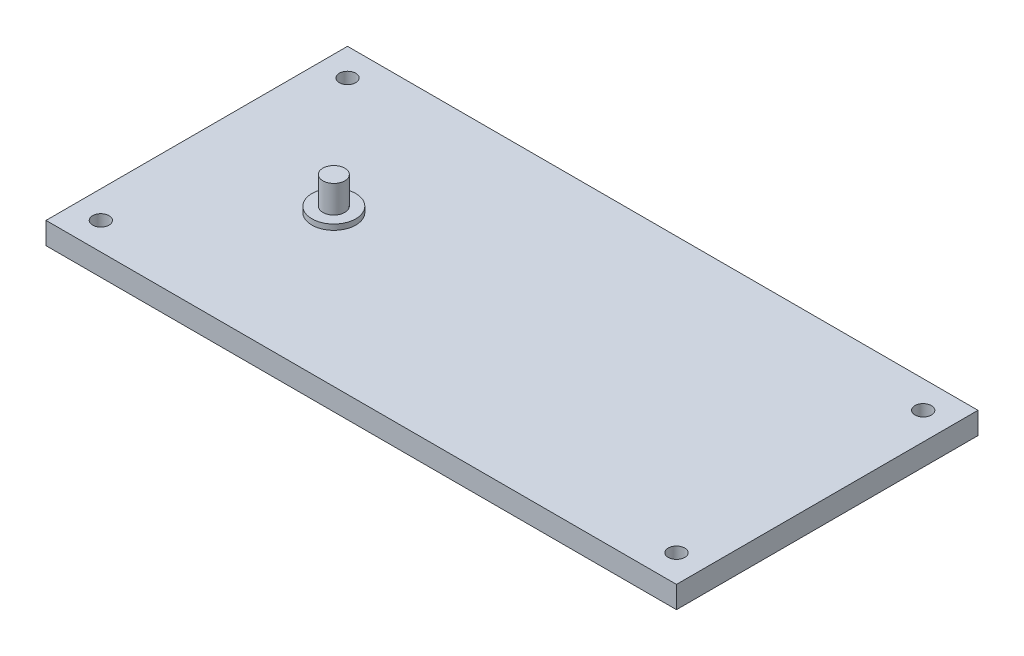
SolidWorks part; units mm, degrees
ref_plane "前视基准面" through (0, 0, 0) normal (0, 0, 1) x (1, 0, 0)
ref_plane "上视基准面" through (0, 0, 0) normal (0, 1, 0) x (1, 0, 0)
ref_plane "右视基准面" through (0, 0, 0) normal (1, 0, 0) x (0, 0, -1)
other "Configuration Table"
sketch "草图1" plane through (0, 0, 0) normal (0, 1, 0) x (1, 0, 0)
  line L1 (-115, 55) -> (115, 55)
  line L2 (-115, 55) -> (-115, -55)
  line L3 (-115, -55) -> (115, -55)
  line L4 (115, 55) -> (115, -55)
  line L5 (-115, 55) -> (115, -55) construction
  line L6 (-115, -55) -> (115, 55) construction
  point P0 (0, 0)
  dimension "D1" = 110
  dimension "D2" = 230
extrude "凸台-拉伸1" add sketch "草图1" along normal blind 8
sketch "草图2" plane through (0, 8, 0) normal (0, 1, 0) x (1, 0, 0)
  circle A0 centre (-65, 0) radius 8
  dimension "D1" = 65
  dimension "D2" = 16
extrude "凸台-拉伸2" add sketch "草图2" along normal blind 2 contours A0
sketch "草图3" plane through (0, 10, 0) normal (0, 1, 0) x (1, 0, 0)
  circle A0 centre (-65, 0) radius 4
  circle A1 centre (-65, 0) radius 8 construction
  dimension "D1" = 8
extrude "凸台-拉伸3" add sketch "草图3" along normal blind 10
sketch "草图4" plane through (0, 8, 0) normal (0, 1, 0) x (1, 0, 0)
  line L0 (-115, 55) -> (-115, -55) construction
  line L2 (115, 55) -> (-115, 55) construction
  line L3 (-115, -55) -> (115, -55) construction
  line L4 (115, -55) -> (115, 55) construction
  circle A0 centre (-105, 45) radius 3
  circle A1 centre (-105, -45) radius 3
  circle A2 centre (105, 45) radius 3
  circle A3 centre (105, -45) radius 3
  point P10 (0, 0)
  point P12 (-104.5278, 49.9713)
  point P13 (-104.052, 55)
  point P19 (0, 0)
  point P22 (103.2439, -40.9811)
  dimension "D1" = 10
  dimension "D9" = 6
  dimension "D10" = 6
  dimension "D11" = 6
  dimension "D12" = 6
  dimension "D2" = 10
  dimension "D3" = 10
  dimension "D4" = 10
  dimension "D5" = 10
  dimension "D6" = 10
  dimension "D7" = 10
  dimension "D8" = 10
extrude "切除-拉伸1" cut sketch "草图4" against normal through all
